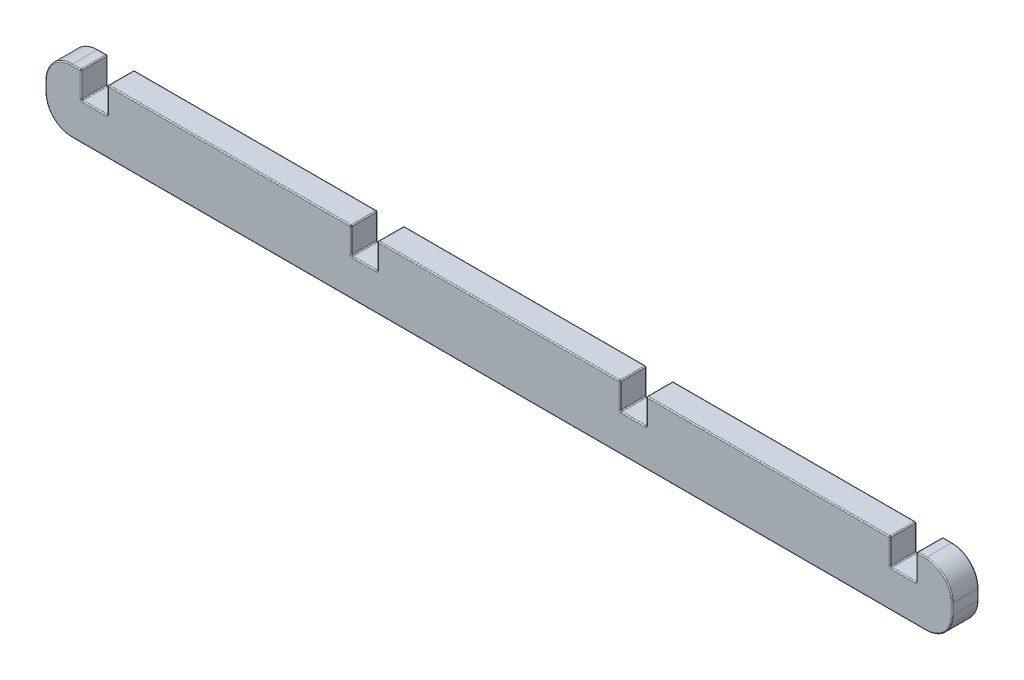
SolidWorks part; units mm, degrees
ref_plane "Plano frontal" through (0, 0, 0) normal (0, 0, 1) x (1, 0, 0)
ref_plane "Plano superior" through (0, 0, 0) normal (0, 1, 0) x (1, 0, 0)
ref_plane "Plano direito" through (0, 0, 0) normal (1, 0, 0) x (0, 0, -1)
sketch "Esboço1" plane through (0, 0, 0) normal (0, 0, 1) x (1, 0, 0)
  line L34 (116.6968, -148.0141) -> (197.6968, -148.0141)
  line L35 (114.1968, -150.5141) -> (114.1968, -151.5141)
  line L36 (116.6968, -154.0141) -> (197.6968, -154.0141)
  line L37 (200.1968, -150.5141) -> (200.1968, -151.5141)
  line L38 (117.5968, -148.0141) -> (120.0968, -148.0141)
  line L39 (117.5968, -148.0141) -> (117.5968, -150.5141)
  line L40 (117.5968, -150.5141) -> (120.0968, -150.5141)
  line L41 (120.0968, -148.0141) -> (120.0968, -150.5141)
  line L42 (143.1968, -148.0141) -> (145.6968, -148.0141)
  line L43 (143.1968, -148.0141) -> (143.1968, -150.5141)
  line L44 (143.1968, -150.5141) -> (145.6968, -150.5141)
  line L45 (145.6968, -148.0141) -> (145.6968, -150.5141)
  line L46 (168.6968, -148.0141) -> (171.1968, -148.0141)
  line L47 (168.6968, -148.0141) -> (168.6968, -150.5141)
  line L48 (168.6968, -150.5141) -> (171.1968, -150.5141)
  line L49 (171.1968, -148.0141) -> (171.1968, -150.5141)
  line L50 (194.2968, -148.0141) -> (196.7968, -148.0141)
  line L51 (194.2968, -148.0141) -> (194.2968, -150.5141)
  line L52 (194.2968, -150.5141) -> (196.7968, -150.5141)
  line L53 (196.7968, -148.0141) -> (196.7968, -150.5141)
  arc A8 (197.6968, -148.0141) -> (200.1968, -150.5141) centre (197.6968, -150.5141) cw
  arc A9 (197.6968, -154.0141) -> (200.1968, -151.5141) centre (197.6968, -151.5141) ccw
  arc A10 (116.6968, -148.0141) -> (114.1968, -150.5141) centre (116.6968, -150.5141) ccw
  arc A11 (114.1968, -151.5141) -> (116.6968, -154.0141) centre (116.6968, -151.5141) ccw
  point P75 (157.1968, -148.0141)
  dimension "D28" = 2.5
  dimension "D21" = 2.5
  dimension "D23" = 11.5
  dimension "D24" = 23
  dimension "D25" = 74.2
  dimension "D26" = 37.1
extrude "Ressalto-extrusão1" add sketch "Esboço1" along normal blind 2.5 contours L35 A11 L36 A9 L37 A8 L34 L53 L52 L51 L49 L48 L47 L45 L44 L43 L41 L40 L39 A10
fillet "Filete1" radius 0.1 64 edges at (196.7968, -148.0141, 1.25) (196.7968, -150.5141, 1.25) (194.2968, -150.5141, 1.25) (194.2968, -148.0141, 1.25) (171.1968, -148.0141, 1.25) (171.1968, -150.5141, 1.25) (168.6968, -150.5141, 1.25) (168.6968, -148.0141, 1.25) (145.6968, -148.0141, 1.25) (145.6968, -150.5141, 1.25) (143.1968, -150.5141, 1.25) (143.1968, -148.0141, 1.25) (120.0968, -148.0141, 1.25) (120.0968, -150.5141, 1.25) (117.5968, -150.5141, 1.25) (117.5968, -148.0141, 1.25) (114.9291, -148.7464, 2.5) (117.1468, -148.0141, 2.5) (117.5968, -149.2641, 2.5) (118.8468, -150.5141, 2.5) (120.0968, -149.2641, 2.5) (131.6468, -148.0141, 2.5) (143.1968, -149.2641, 2.5) (144.4468, -150.5141, 2.5) (145.6968, -149.2641, 2.5) (157.1968, -148.0141, 2.5) (168.6968, -149.2641, 2.5) (169.9468, -150.5141, 2.5) (171.1968, -149.2641, 2.5) (182.7468, -148.0141, 2.5) (194.2968, -149.2641, 2.5) (195.5468, -150.5141, 2.5) (196.7968, -149.2641, 2.5) (197.2468, -148.0141, 2.5) (199.4646, -148.7464, 2.5) (200.1968, -151.0141, 2.5) (199.4646, -153.2819, 2.5) (157.1968, -154.0141, 2.5) (114.9291, -153.2819, 2.5) (114.1968, -151.0141, 2.5) (114.9291, -153.2819, 0) (157.1968, -154.0141, 0) (199.4646, -153.2819, 0) (200.1968, -151.0141, 0) (199.4646, -148.7464, 0) (197.2468, -148.0141, 0) (196.7968, -149.2641, 0) (195.5468, -150.5141, 0) (194.2968, -149.2641, 0) (182.7468, -148.0141, 0) (171.1968, -149.2641, 0) (169.9468, -150.5141, 0) (168.6968, -149.2641, 0) (157.1968, -148.0141, 0) (145.6968, -149.2641, 0) (144.4468, -150.5141, 0) (143.1968, -149.2641, 0) (131.6468, -148.0141, 0) (120.0968, -149.2641, 0) (118.8468, -150.5141, 0) (117.5968, -149.2641, 0) (117.1468, -148.0141, 0) (114.9291, -148.7464, 0) (114.1968, -151.0141, 0)
